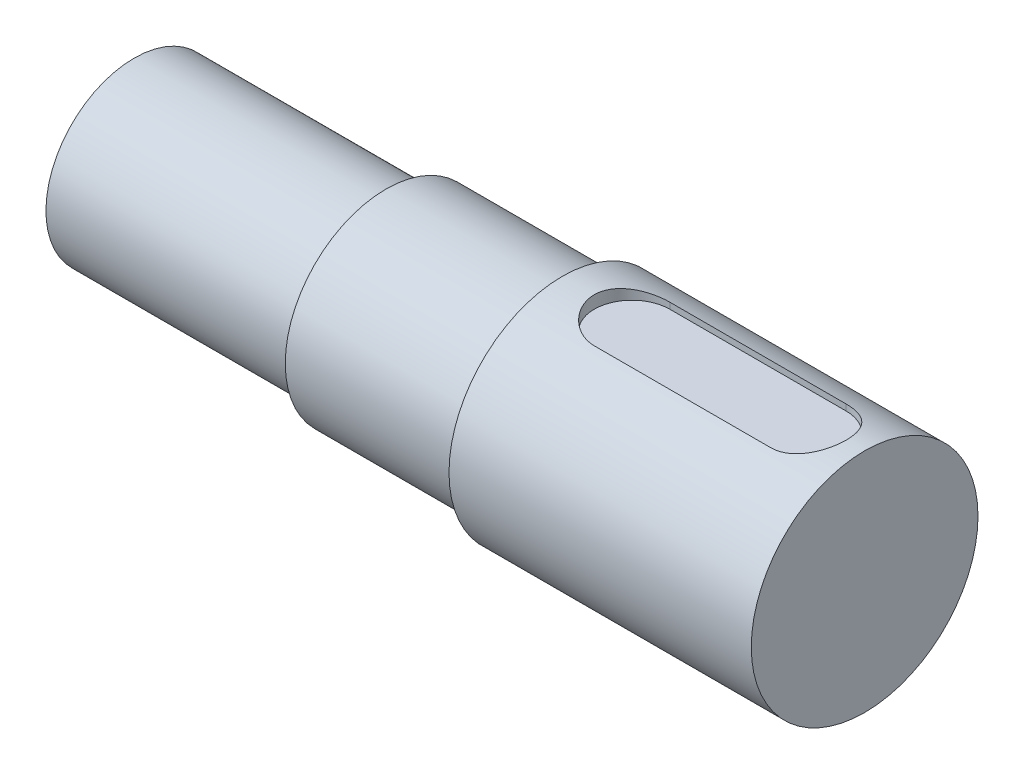
SolidWorks part; units mm, degrees
ref_plane "Front Plane" through (0, 0, 0) normal (0, 0, 1) x (1, 0, 0)
ref_plane "Top Plane" through (0, 0, 0) normal (0, 1, 0) x (1, 0, 0)
ref_plane "Right Plane" through (0, 0, 0) normal (1, 0, 0) x (0, 0, -1)
sketch "Sketch1" plane through (0, 0, 0) normal (0, 0, 1) x (1, 0, 0)
  line L0 (0, 0) -> (0, 3.5)
  line L1 (0, 3.5) -> (10, 3.5)
  line L2 (10, 3.5) -> (10, 4)
  line L3 (10, 4) -> (17, 4)
  line L4 (17, 4) -> (17, 4.5)
  line L5 (17, 4.5) -> (29, 4.5)
  line L6 (29, 4.5) -> (29, 0)
  line L7 (29, 0) -> (0, 0)
  dimension "D1" = 3.5
  dimension "D2" = 10
  dimension "D3" = 4
  dimension "D4" = 4.5
  dimension "D5" = 7
  dimension "D6" = 12
revolve "Revolve1" add sketch "Sketch1" angle 360 about L7
sketch "Sketch2" plane through (0, 0, 0) normal (0, 1, 0) x (1, 0, 0)
  line L0 (29, 0) -> (-0.9611, 0) construction
  line L1 (29, -4.5) -> (29, 4.5) construction
  line L2 (19.7666, 0) -> (26.7666, 0) construction
  line L3 (19.7666, 1.5) -> (26.7666, 1.5)
  line L4 (19.7666, -1.5) -> (26.7666, -1.5)
  arc A0 (19.7666, 1.5) -> (19.7666, -1.5) centre (19.7666, 0) ccw
  arc A1 (26.7666, -1.5) -> (26.7666, 1.5) centre (26.7666, 0) ccw
  point P7 (23.2666, 0)
  dimension "D1" = 1.5
  dimension "D2" = 7
extrude "Cut-Extrude1" cut sketch "Sketch2" along normal blind 10 from offset 4
